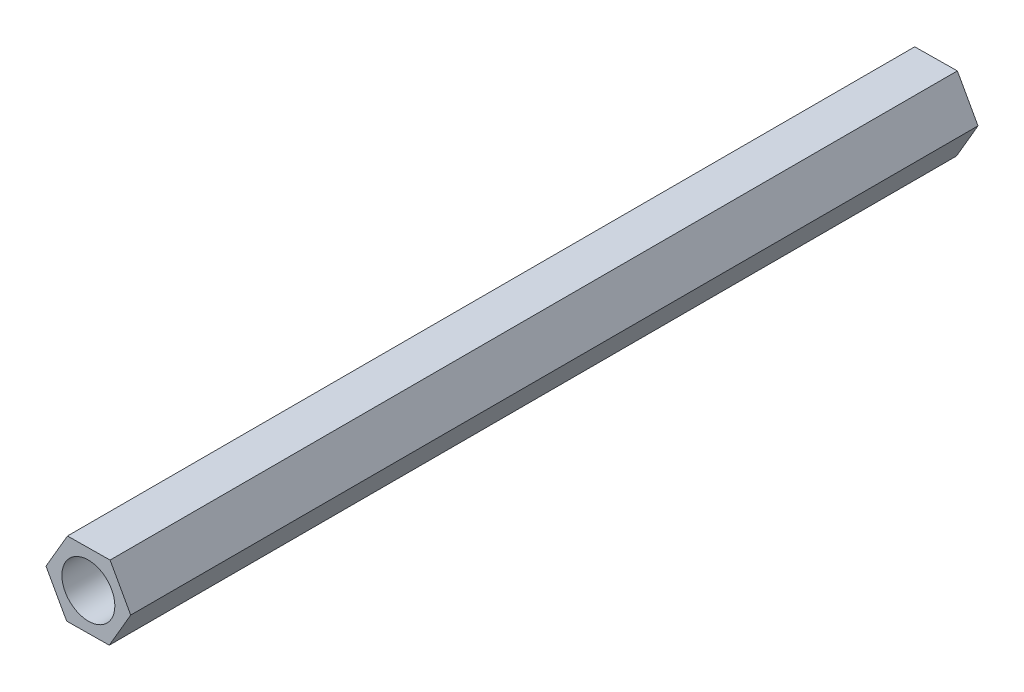
SolidWorks part; units mm, degrees
ref_plane "前视基准面" through (0, 0, 0) normal (0, 0, 1) x (1, 0, 0)
ref_plane "上视基准面" through (0, 0, 0) normal (0, 1, 0) x (1, 0, 0)
ref_plane "右视基准面" through (0, 0, 0) normal (1, 0, 0) x (0, 0, -1)
other "Configuration Table"
sketch "草图1" plane through (0, 0, 0) normal (0, 0, 1) x (1, 0, 0)
  line L0 (-1.9743, 3.4788) -> (2.0511, 3.5224)
  line L1 (2.0511, 3.5224) -> (4, 0)
  line L2 (4, 0) -> (1.9743, -3.4788)
  line L3 (1.9743, -3.4788) -> (-2.0511, -3.5224)
  line L4 (-2.0511, -3.5224) -> (-4, 0)
  line L5 (-4, 0) -> (-1.9743, 3.4788)
  line L6 (-1.9743, 3.4788) -> (1.9743, -3.4788) construction
  line L7 (-4, 0) -> (4, 0) construction
  circle A0 centre (0, 0) radius 2.5
  point P9 (0, 0)
  point P10 (3.9914, -0.2618)
  dimension "D4" = 5
  dimension "D1" = 7
  dimension "D2" = 8
  dimension "D3" = 7
extrude "凸台-拉伸1" add sketch "草图1" along normal blind 80
